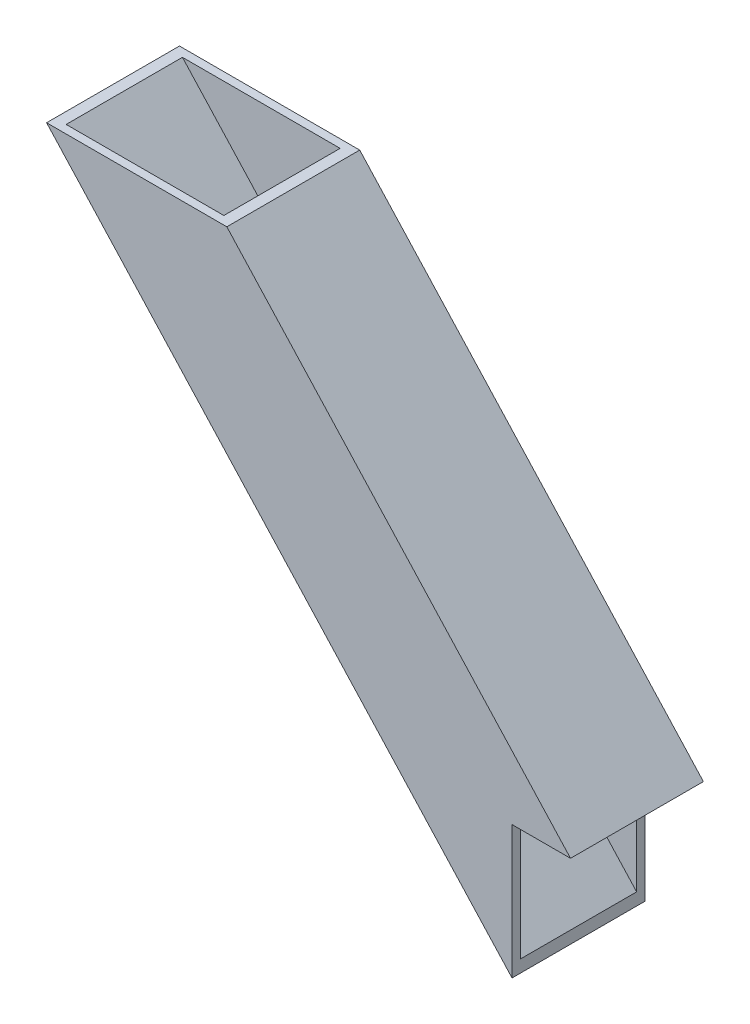
SolidWorks part; units mm, degrees
ref_plane "Front Plane" through (0, 0, 0) normal (0, 0, 1) x (1, 0, 0)
ref_plane "Top Plane" through (0, 0, 0) normal (0, 1, 0) x (1, 0, 0)
ref_plane "Right Plane" through (0, 0, 0) normal (1, 0, 0) x (0, 0, -1)
sketch "Sketch1" plane through (0, 0, 0) normal (0, 0, 1) x (1, 0, 0)
  line L6 (-6.3295, -89.7795) -> (-184.2679, 104.4061)
  line L7 (-184.2679, 104.4061) -> (-115.3657, 104.4061)
  line L8 (-115.3657, 104.4061) -> (16.023, -38.9795)
  line L9 (-6.3295, -38.9795) -> (16.023, -38.9795)
  line L11 (-6.3295, -89.7795) -> (-6.3295, -38.9795)
  dimension "D1" = 50.8
  dimension "D2" = 42.5
  dimension "D3" = 50.8
extrude "Boss-Extrude1" add sketch "Sketch1" along normal blind 50.8
ref_plane "Plane2" through (0, 0, 25.4) normal (0, 0, 1) x (1, 0, 0)
sketch "Sketch13" plane through (0, 0, 25.4) normal (0, 0, 1) x (1, 0, 0)
  line L1 (-149.8168, 104.4061) -> (41.275, -104.1339)
  line L3 (-115.3657, 104.4061) -> (-184.2679, 104.4061) construction
  line L4 (-184.2679, 104.4061) -> (-148.5437, 65.42)
  line L5 (-184.2679, 104.4061) -> (-6.3295, -89.7795) construction
  point P0 (-184.2679, 104.4061)
sketch "Sketch14" plane through (0, 104.4061, 0) normal (0, 1, 0) x (1, 0, 0)
  line L0 (-184.2679, -50.8) -> (-184.2679, 0) construction
  line L1 (-119.6721, -3.175) -> (-179.9615, -3.175)
  line L2 (-119.6721, -3.175) -> (-119.6721, -47.625)
  line L3 (-119.6721, -47.625) -> (-179.9615, -47.625)
  line L4 (-179.9615, -3.175) -> (-179.9615, -47.625)
  line L5 (-115.3657, 0) -> (-184.2679, 0) construction
  line L6 (-115.3657, -50.8) -> (-184.2679, -50.8) construction
  line L7 (-179.9615, -3.175) -> (-119.6721, -47.625) construction
  line L8 (-119.6721, -3.175) -> (-179.9615, -47.625) construction
  line L9 (-115.3657, -50.8) -> (-115.3657, 0) construction
  dimension "D1" = 3.175
  dimension "D2" = 3.175
  dimension "D3" = 4.3064
  dimension "D4" = 4.3064
sweep "Cut-Sweep1" cut profiles "Sketch14" path "Sketch13"
equation "\"D3@Sketch14\"=0.125/cos(42.5)"
equation "\"D4@Sketch14\"= \"D3@Sketch14\""
